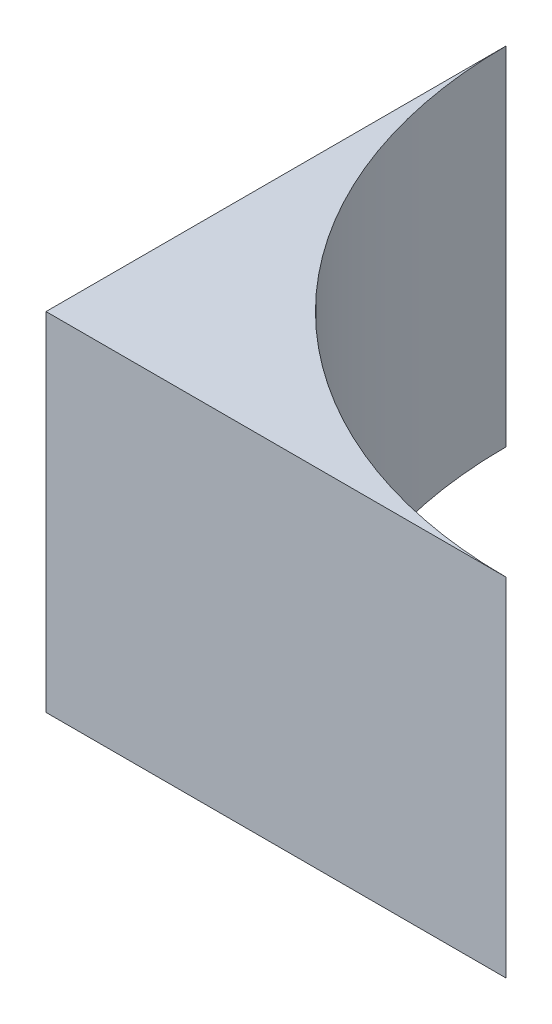
SolidWorks part; units mm, degrees
ref_plane "Front Plane" through (0, 0, 0) normal (0, 0, 1) x (1, 0, 0)
ref_plane "Top Plane" through (0, 0, 0) normal (0, 1, 0) x (1, 0, 0)
ref_plane "Right Plane" through (0, 0, 0) normal (1, 0, 0) x (0, 0, -1)
sketch "Sketch2" plane through (0, 0, 0) normal (0, 1, 0) x (1, 0, 0)
  line L0 (0, -64.25) -> (-64.25, -64.25)
  line L1 (-64.25, -64.25) -> (-64.25, 0)
  arc A0 (-64.25, 0) -> (0, -64.25) centre (0, 0) ccw
  dimension "D1" = 128.5
extrude "Boss-Extrude1" add sketch "Sketch2" along normal blind 48.5
